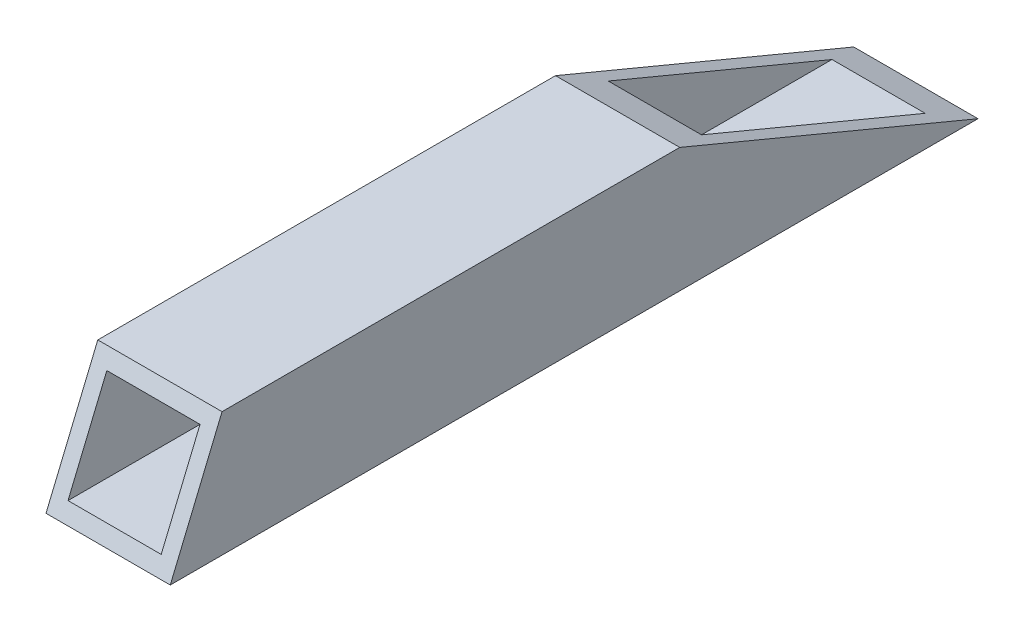
SolidWorks part; units mm, degrees
ref_plane "Front Plane" through (0, 0, 0) normal (0, 0, 1) x (1, 0, 0)
ref_plane "Top Plane" through (0, 0, 0) normal (0, 1, 0) x (1, 0, 0)
ref_plane "Right Plane" through (0, 0, 0) normal (1, 0, 0) x (0, 0, -1)
sketch "Sketch1" plane through (0, 0, 0) normal (0, 0, 1) x (1, 0, 0)
  line L1 (0, 0) -> (25.4, 0)
  line L2 (0, 0) -> (0, 25.4)
  line L3 (0, 25.4) -> (25.4, 25.4)
  line L4 (25.4, 0) -> (25.4, 25.4)
  line L5 (3.175, 22.225) -> (22.225, 22.225)
  line L6 (3.175, 22.225) -> (3.175, 3.175)
  line L7 (3.175, 3.175) -> (22.225, 3.175)
  line L8 (22.225, 22.225) -> (22.225, 3.175)
  dimension "D1" = 25.4
  dimension "D2" = 25.4
  dimension "D3" = 3.175
  dimension "D4" = 3.175
  dimension "D5" = 3.175
  dimension "D6" = 3.175
extrude "Boss-Extrude2" add sketch "Sketch1" along normal blind 165.1
sketch "Sketch3" plane through (25.4, 0, 0) normal (1, 0, 0) x (0, 0, -1)
  line L0 (-165.1, 0) -> (-154.5166, 25.4)
  line L1 (-165.1, 25.4) -> (0, 25.4) construction
  line L2 (-165.1, 0) -> (-165.1, 25.4) construction
  line L3 (0, 0) -> (-60.9596, 25.4)
  line L4 (0, 0) -> (0, 25.4) construction
  line L5 (-165.1, 25.4) -> (-154.5166, 25.4)
  line L6 (0, 0) -> (0, 25.4)
  line L7 (-165.1, 0) -> (-165.1, 25.4)
  line L8 (-60.9596, 25.4) -> (0, 25.4)
  dimension "D1" = 22.62
  dimension "D2" = 67.38
extrude "Cut-Extrude1" cut sketch "Sketch3" against normal up to surface (25.4 mm away) up to face at (0, 12.7, 82.55)
